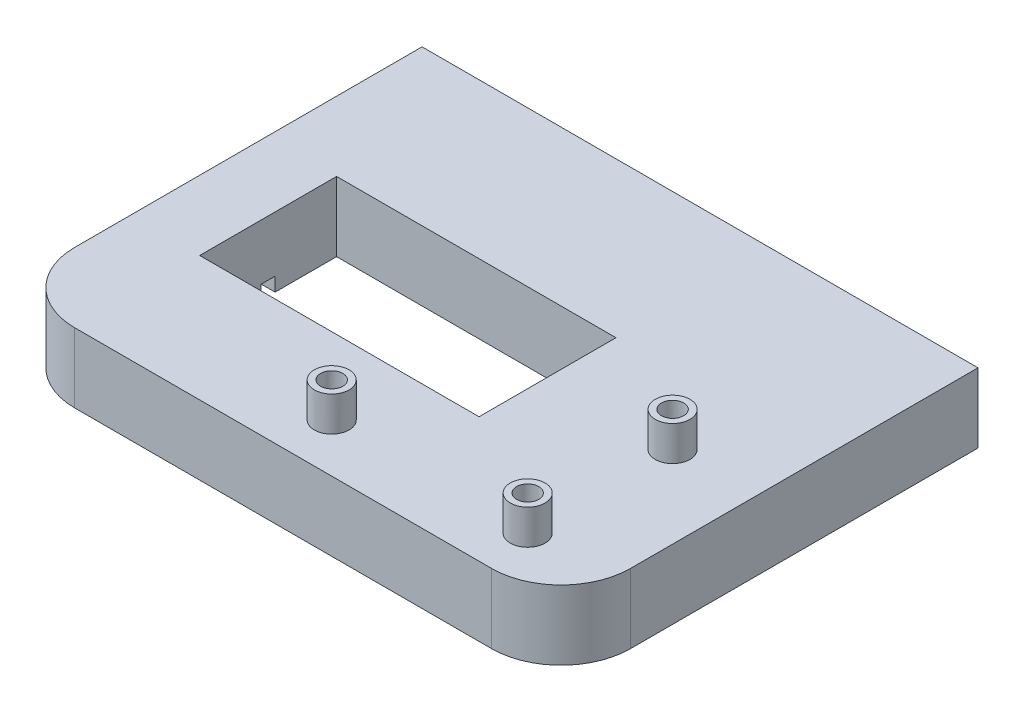
SolidWorks part; units mm, degrees
ref_plane "Front Plane" through (0, 0, 0) normal (0, 0, 1) x (1, 0, 0)
ref_plane "Top Plane" through (0, 0, 0) normal (0, 1, 0) x (1, 0, 0)
ref_plane "Right Plane" through (0, 0, 0) normal (1, 0, 0) x (0, 0, -1)
sketch "Sketch2" plane through (0, 0, 0) normal (0, 1, 0) x (1, 0, 0)
  line L1 (-40, -30) -> (40, -30)
  line L2 (-40, -30) -> (-40, 30)
  line L3 (-40, 30) -> (40, 30)
  line L4 (40, -30) -> (40, 30)
  line L5 (-40, -30) -> (40, 30) construction
  line L6 (-40, 30) -> (40, -30) construction
  point P0 (0, 0)
  dimension "D1" = 60
  dimension "D2" = 80
extrude "Boss-Extrude1" add sketch "Sketch2" along normal blind 10
sketch "Sketch3" plane through (0, 10, 0) normal (0, 1, 0) x (1, 0, 0)
  line L0 (-40, 30) -> (-40, -30) construction
  line L1 (-30, -12) -> (10.2, -12)
  line L2 (-30, -12) -> (-30, 7.7)
  line L3 (-30, 7.7) -> (10.2, 7.7)
  line L4 (10.2, -12) -> (10.2, 7.7)
  line L5 (-30, -12) -> (10.2, 7.7) construction
  line L6 (-30, 7.7) -> (10.2, -12) construction
  line L8 (-40, -30) -> (40, -30) construction
  point P0 (-9.9, -2.15)
  dimension "D1" = 19.7
  dimension "D2" = 40.2
  dimension "D3" = 10
  dimension "D4" = 18
extrude "Cut-Extrude1" cut sketch "Sketch3" against normal blind 10
fillet "Fillet1" radius 10 2 edges at (40, 5, 30) (-40, 5, 30)
sketch "Sketch4" plane through (0, 10, 0) normal (0, 1, 0) x (1, 0, 0)
  line L0 (10.2, -2.15) -> (40, -2.15) construction
  line L1 (10.2, -12) -> (10.2, 7.7) construction
  line L2 (40, -20) -> (40, 30) construction
  line L3 (0, -30) -> (0, 30) construction
  line L4 (-30, -30) -> (30, -30) construction
  line L5 (40, 30) -> (-40, 30) construction
  line L6 (0, -23) -> (28.2, -23) construction
  line L7 (28.2, -2.15) -> (28.2, -30) construction
  circle A0 centre (28.2, -2.15) radius 1.6
  circle A1 centre (28.2, -2.15) radius 2.5
  circle A2 centre (0, -23) radius 1.6
  circle A3 centre (0, -23) radius 2.5
  circle A4 centre (28.2, -23) radius 1.6
  circle A5 centre (28.2, -23) radius 2.5
  dimension "D1" = 3.2
  dimension "D2" = 5
  dimension "D3" = 3.2
  dimension "D4" = 5
  dimension "D5" = 3.2
  dimension "D6" = 5
  dimension "D7" = 7
  dimension "D9" = 18
extrude "Boss-Extrude2" add sketch "Sketch4" along normal blind 5
sketch "Sketch5" plane through (0, 10, 0) normal (0, 1, 0) x (1, 0, 0)
  circle A0 centre (0, -23) radius 1.6
  circle A1 centre (28.2, -23) radius 1.6
  circle A2 centre (28.2, -2.15) radius 1.6
extrude "Cut-Extrude2" cut sketch "Sketch5" against normal blind 21
sketch "Sketch7" plane through (0, 0, 0) normal (0, -1, 0) x (1, 0, 0)
  line L0 (-40.2804, 2.15) -> (-35.0705, 2.15) construction
  line L1 (-37.4, 3.15) -> (17.6, 3.15)
  line L2 (-37.4, 3.15) -> (-37.4, 1.15)
  line L3 (-37.4, 1.15) -> (17.6, 1.15)
  line L4 (17.6, 3.15) -> (17.6, 1.15)
  line L5 (-30, -7.7) -> (-30, 12) construction
  line L6 (10.2, 12) -> (10.2, -7.7) construction
  line L8 (-35.0705, 2.15) -> (10.2, 2.15) construction
  line L9 (10.2, 2.15) -> (17.6, 2.15) construction
  line L10 (-9.9, 12) -> (-9.9, 3.15) construction
  line L11 (-30, 12) -> (10.2, 12) construction
  line L12 (-9.9, 3.15) -> (-9.9, 1.15) construction
  line L13 (-9.9, 1.15) -> (-9.9, -7.7) construction
  line L14 (10.2, -7.7) -> (-30, -7.7) construction
  point P6 (-30, 2.15)
  point P7 (10.2, 2.15)
  dimension "D1" = 55
  dimension "D2" = 2
extrude "Cut-Extrude3" cut sketch "Sketch7" against normal blind 2
sketch "Sketch8" plane through (0, 0, 0) normal (0, -1, 0) x (1, 0, 0)
  line L1 (3.4641, 23) -> (1.7321, 26)
  line L2 (1.7321, 26) -> (-1.7321, 26)
  line L3 (-1.7321, 26) -> (-3.4641, 23)
  line L4 (-3.4641, 23) -> (-1.7321, 20)
  line L5 (-1.7321, 20) -> (1.7321, 20)
  line L6 (1.7321, 20) -> (3.4641, 23)
  line L7 (31.6641, 23) -> (29.9321, 26)
  line L8 (29.9321, 26) -> (26.4679, 26)
  line L9 (26.4679, 26) -> (24.7359, 23)
  line L10 (24.7359, 23) -> (26.4679, 20)
  line L11 (26.4679, 20) -> (29.9321, 20)
  line L12 (29.9321, 20) -> (31.6641, 23)
  line L13 (31.6641, 2.15) -> (29.9321, 5.15)
  line L14 (29.9321, 5.15) -> (26.4679, 5.15)
  line L15 (26.4679, 5.15) -> (24.7359, 2.15)
  line L16 (24.7359, 2.15) -> (26.4679, -0.85)
  line L17 (26.4679, -0.85) -> (29.9321, -0.85)
  line L18 (29.9321, -0.85) -> (31.6641, 2.15)
  circle A0 centre (0, 23) radius 3 construction
  circle A1 centre (28.2, 23) radius 3 construction
  circle A2 centre (28.2, 2.15) radius 3 construction
  dimension "D1" = 6
  dimension "D2" = 6
  dimension "D3" = 6
extrude "Cut-Extrude4" cut sketch "Sketch8" against normal blind 3
